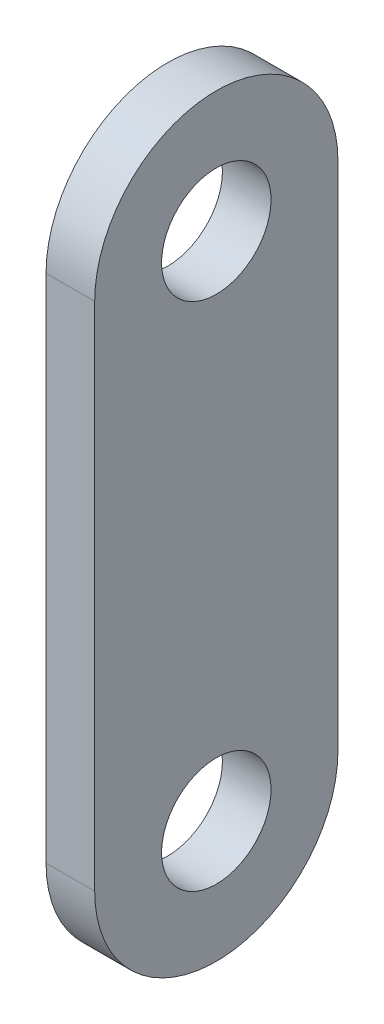
SolidWorks part; units mm, degrees
material "Plain Carbon Steel"
ref_plane "Front Plane" through (0, 0, 0) normal (0, 0, 1) x (1, 0, 0)
ref_plane "Top Plane" through (0, 0, 0) normal (0, 1, 0) x (1, 0, 0)
ref_plane "Right Plane" through (0, 0, 0) normal (1, 0, 0) x (0, 0, -1)
sketch "Sketch1" plane through (0, 0, 0) normal (1, 0, 0) x (0, 0, -1)
  line L0 (0, 0) -> (0, -66.675) construction
  line L1 (15.875, 0) -> (15.875, -66.675)
  line L2 (-15.875, 0) -> (-15.875, -66.675)
  arc A0 (15.875, 0) -> (-15.875, 0) centre (0, 0) ccw
  arc A1 (-15.875, -66.675) -> (15.875, -66.675) centre (0, -66.675) ccw
  circle A2 centre (0, 0) radius 7.1438
  circle A3 centre (0, -66.675) radius 7.1438
  point P2 (0, -33.3375)
  dimension "D3" = 14.2875
  dimension "D1" = 31.75
  dimension "D2" = 66.675
extrude "Boss-Extrude1" add sketch "Sketch1" along normal blind 6.35
